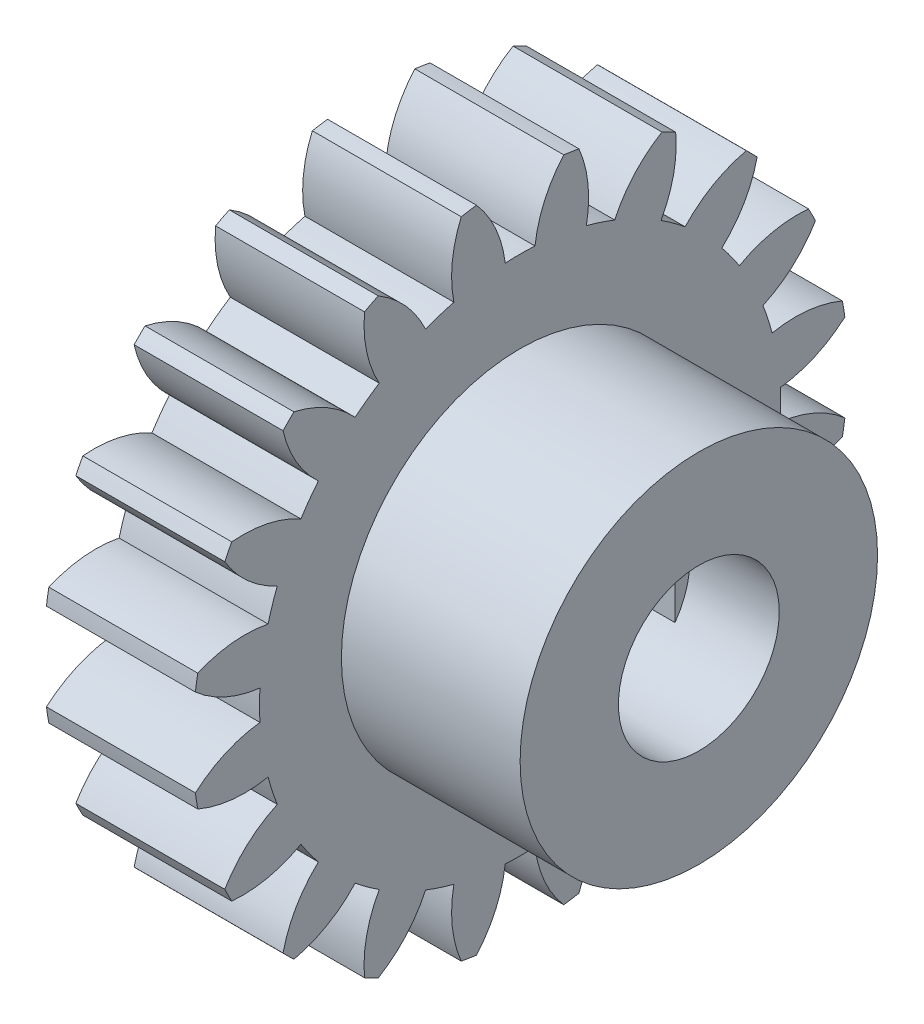
SolidWorks part; units mm, degrees
ref_plane "Plane1" through (0, 0, 0) normal (0, 0, 1) x (1, 0, 0)
ref_plane "Plane2" through (0, 0, 0) normal (0, 1, 0) x (1, 0, 0)
ref_plane "Plane3" through (0, 0, 0) normal (1, 0, 0) x (0, 0, -1)
sketch "HoldingSke" plane through (0, 0, 0) normal (0, 1, 0) x (1, 0, 0)
  line L0 (0, 0) -> (0.9397, -0.342)
  line L1 (-15, 0) -> (100, 0) construction
  line L2 (0, 0) -> (-2.1039, 2.3779)
  line L3 (0, 0) -> (-11.863, 4.5341)
  line L4 (0, 0) -> (8.1152, 2.9537)
  line L5 (0, 0) -> (-46.8476, -17.4728)
  line L6 (0, 0) -> (-8.2896, -5.593)
  line L7 (-2.1039, 2.3779) -> (8.6586, 51.2059)
  line L8 (-76.2, 54.61) -> (-75.7, 54.61)
  line L9 (-71.009, 38.7566) -> (-53.1078, 45.2721)
  line L10 (-76.2, 71.12) -> (104.1128, 71.12)
  line L11 (0, 0) -> (-10, 0)
  line L12 (-76.2, 101.6) -> (-76.162, 101.6)
  line L13 (24.9733, 27.94) -> (52.9518, 28.4284)
  line L14 (24.9733, 27.94) -> (24.9743, 27.94)
  line L15 (24.9733, 27.94) -> (100.4006, 29.5858)
  line L16 (-63.627, -1) -> (-12.827, -1)
  circle A0 centre (0, 0) radius 1.5
  circle A1 centre (0, 0) radius 8.749
  circle A2 centre (0, 0) radius 37.5
  circle A3 centre (0, 0) radius 1.5
  dimension "MHD" = 17.498
  dimension "Hub_dia" = 75
  dimension "Bore" = 3
  dimension "MBD" = 3
  dimension "Num_teeth" = 20
  dimension "Pitch" = 1
  dimension "Overall_len" = 50
  dimension "Show_teeth" = 20
  dimension "Thickness" = 10
  dimension "OAL" = 50.0001
  dimension "T_dim" = 0.5
  dimension "Ap" = 20
  dimension "H" = 19.05
  dimension "Pitch_radius" = 180.3128
  dimension "Width" = 10
  dimension "Backlash" = 0.038
  dimension "Addendum_fac" = 1
  dimension "Dedendum_fac" = 1.25
  dimension "Clearance_fac" = 0.25
  dimension "Dedendum_add" = 0.001
  dimension "Module" = 1
sketch "BasProSke" plane through (0, 0, 0) normal (0, 1, 0) x (1, 0, 0)
  line L0 (-10, 0) -> (60, 0) construction
  line L1 (0, 0) -> (0, 11)
  line L2 (0, 0) -> (5, 0)
  line L3 (5, 0) -> (5, 11)
  line L4 (5, 11) -> (0, 11)
  dimension "Thickness" = 5
  dimension "Diameter" = 22
revolve "Base-Revolve" add sketch "BasProSke" angle 360 about L0
sketch "TooCutSke" plane through (0, 0, 0) normal (1, 0, 0) x (0, 0, -1)
  line L1 (0, 0) -> (0, 107) construction
  line L2 (0, 0) -> (-0.8511, 9.9637) construction
  line L3 (0, 0) -> (-3.1206, 19.7028) construction
  line L4 (-0.8511, 9.9637) -> (-1.5603, 9.8514) construction
  arc A0 (0.4999, 8.7347) -> (-0.4999, 8.7347) centre (0, 0) ccw
  arc A1 (1.4852, 10.9249) -> (-1.4852, 10.9249) centre (0, 0) ccw
  circle A2 centre (0, 0) radius 10 construction
  circle A3 centre (0, 0) radius 9.3969 construction
  arc A4 (-0.4999, 8.7347) -> (-1.4852, 10.9249) centre (-4.4722, 8.2645) ccw
  arc A5 (1.4852, 10.9249) -> (0.4999, 8.7347) centre (4.4722, 8.2645) ccw
  dimension "Root_dia" = 17.498
  dimension "Overcut_dia" = 22.0508
  dimension "Pitch_dia" = 20
  dimension "Base_dia" = 18.7939
  dimension "Flank_rad" = 4
  dimension "Half_ang" = 9
  dimension "Half_CT" = 0.7181
extrude "ToothCut" cut sketch "TooCutSke" along normal through all
fillet "Breaks" [suppressed] radius 0.02
fillet "RootFillets" [suppressed] radius 0.251
pattern_circular "TeethCuts" count 20 over 360 about axis through (0, 0, 0) along (1, 0, 0) of "ToothCut", "RootFillets", "Breaks"
sketch "HubNeaOneSke" plane through (0, 0, 0) normal (-1, 0, 0) x (0, 0, 1)
  circle A0 centre (0, 0) radius 8.749
  dimension "Diameter" = 17.498
extrude "HubNearOne" [suppressed] add sketch "HubNeaOneSke" along normal blind 45.0001
sketch "HubNeaBotSke" plane through (0, 0, 0) normal (-1, 0, 0) x (0, 0, 1)
  circle A0 centre (0, 0) radius 8.749
  dimension "Diameter" = 17.498
extrude "HubNearBoth" [suppressed] add sketch "HubNeaBotSke" along normal blind 22.5
ref_plane "FarPln" through (5, 0, 0) normal (1, 0, 0) x (0, 0, -1)
sketch "HubFarSke" plane through (5, 0, 0) normal (1, 0, 0) x (0, 0, -1)
  circle A0 centre (0, 0) radius 8.749
  dimension "Diameter" = 17.498
extrude "HubFar" [suppressed] add sketch "HubFarSke" along normal blind 22.5
sketch "BorSke" plane through (0, 0, 0) normal (1, 0, 0) x (0, 0, -1)
  circle A0 centre (0, 0) radius 1.5
  dimension "Diameter" = 3
extrude "Bore" cut sketch "BorSke" along normal mid plane 100.0001
sketch "KeySke" plane through (0, 0, 0) normal (1, 0, 0) x (0, 0, -1)
  line L0 (-0.6, 0) -> (-0.6, 2)
  line L1 (-0.6, 2) -> (0.6, 2)
  line L2 (0.6, 2) -> (0.6, 0)
  line L3 (0, 0) -> (0, 34) construction
  line L4 (-0.6, 0) -> (0.6, 0)
  dimension "Offset" = 2
  dimension "Width" = 1.2
extrude "Keyway" [suppressed] cut sketch "KeySke" along normal mid plane 100.0001
pattern_circular "Keyway2" [suppressed] count 2 every 90 about axis through (-10, 0, 0) along (1, 0, 0)
sketch "草图1" plane through (5, 0, 0) normal (1, 0, 0) x (0, 0, -1)
  circle A0 centre (0, 0) radius 6
  dimension "D1" = 12
extrude "凸台-拉伸1" add sketch "草图1" along normal blind 6
sketch "草图2" plane through (11, 0, 0) normal (1, 0, 0) x (0, 0, -1)
  line L0 (2.2, 1.5652) -> (2.2, -1.5652)
  arc A0 (2.2, 1.5652) -> (2.2, -1.5652) centre (0, 0) ccw
  dimension "D1" = 5.4
  dimension "D2" = 2.2
extrude "切除-拉伸1" cut sketch "草图2" against normal blind 14
sketch "草图3" plane through (11, 0, 0) normal (1, 0, 0) x (0, 0, -1)
  circle A0 centre (0, 0) radius 2.7
extrude "切除-拉伸2" cut sketch "草图3" against normal blind 3
equation "' \"Module@HoldingSke\" = 6.35"
equation "' \"Num_teeth@HoldingSke\" = 12"
equation "' \"Ap@HoldingSke\" =  20"
equation "' \"Ap@HoldingSke\" = 20"
equation "' \"Width@HoldingSke\" = 0.5 * 25.4"
equation "' \"Hub_dia@HoldingSke\"= 1 * 25.4"
equation "' \"Hub_dia@HoldingSke\" = 1 * 25.4"
equation "' \"Overall_len@HoldingSke\" = 1.0 * 25.4"
equation "' \"Bore@HoldingSke\" = 0.75 * 25.4"
equation "' \"T_dim@HoldingSke\" = 0.1 * 25.4"
equation "' \"Width@KeySke\" = 0.25 * 25.4"
equation "' \"Show_teeth@HoldingSke\" = 13"
equation "' \"Backlash@HoldingSke\" = 0.009 * 25.4"
equation "' \"Addendum_fac@HoldingSke\" = 1.0"
equation "' \"Dedendum_fac@HoldingSke\" = 1.25"
equation "' \"Dedendum_add@HoldingSke\" = 0.00005 * 25.4"
equation "' \"Clearance_fac@HoldingSke\" = 0.25"
equation "\"Pitch@HoldingSke\" = 1 / \"Module@HoldingSke\""
equation "\"Overcut_dia@TooCutSke\" = (\"Num_teeth@HoldingSke\" + 2 * \"Addendum_fac@HoldingSke\") / \"Pitch@HoldingSke\" + 0.002 * 25.4"
equation "\"Pitch_dia@TooCutSke\" = \"Num_teeth@HoldingSke\" / \"Pitch@HoldingSke\""
equation "\"Base_dia@TooCutSke\" = \"Num_teeth@HoldingSke\" / \"Pitch@HoldingSke\" * cos((\"Ap@HoldingSke\"  * 3.14159265 / 180))"
equation "\"Root_dia@TooCutSke\" = (\"Num_teeth@HoldingSke\" + 2) / \"Pitch@HoldingSke\" - 2 * (\"Addendum_fac@HoldingSke\" + \"Dedendum_fac@HoldingSke\") / \"Pitch@HoldingSke\" - \"Dedendum_add@HoldingSke\" * 2"
equation "\"Half_ang@TooCutSke\" = 180 / \"Num_teeth@HoldingSke\""
equation "\"Half_CT@TooCutSke\" = \"Num_teeth@HoldingSke\" / \"Pitch@HoldingSke\" * sin((3.14159265 / 2 / \"Num_teeth@HoldingSke\")) / 2 - 7 * \"Backlash@HoldingSke\" / 4"
equation "\"Flank_rad@TooCutSke\" = \"Num_teeth@HoldingSke\" / \"Pitch@HoldingSke\" / 5"
equation "\"Radius@RootFillets\" = \"Clearance_fac@HoldingSke\" / \"Pitch@HoldingSke\" + \"Dedendum_add@HoldingSke\""
equation "\"Break_rad@Breaks\" = 0.02 / \"Pitch@HoldingSke\""
equation "\"Thickness@HoldingSke\" = \"Width@HoldingSke\""
equation "\"OAL@HoldingSke\" = \"Thickness@HoldingSke\""
equation "\"MHD@HoldingSke\" = (\"Num_teeth@HoldingSke\" + 2) / \"Pitch@HoldingSke\" - 2 * (\"Addendum_fac@HoldingSke\" + \"Dedendum_fac@HoldingSke\")  / \"Pitch@HoldingSke\" - \"Dedendum_add@HoldingSke\" * 2"
equation "\"MBD@HoldingSke\" = (\"Num_teeth@HoldingSke\" + 2) / \"Pitch@HoldingSke\" - 2 * (\"Addendum_fac@HoldingSke\" + \"Dedendum_fac@HoldingSke\")  / \"Pitch@HoldingSke\" - \"Dedendum_add@HoldingSke\" * 2 - 0.002 * 25.4"
equation "\"MHD@HoldingSke\" = ((sgn( \"MHD@HoldingSke\" - \"Hub_dia@HoldingSke\" )-1)*( \"MHD@HoldingSke\" - \"Hub_dia@HoldingSke\" ))/-2+ \"Hub_dia@HoldingSke\""
equation "\"MBD@HoldingSke\" = ((sgn( \"MBD@HoldingSke\" - \"Bore@HoldingSke\" )-1)*( \"MBD@HoldingSke\" - \"Bore@HoldingSke\" ))/-2+ \"Bore@HoldingSke\""
equation "\"OAL@HoldingSke\" = ((sgn( \"OAL@HoldingSke\" - \"Overall_len@HoldingSke\" )+1)*( \"OAL@HoldingSke\" - \"Overall_len@HoldingSke\" ))/2 + \"Overall_len@HoldingSke\" + 0.000002 * 25.4"
equation "\"Num_teeth@TeethCuts\" = int( \"Show_teeth@HoldingSke\" ) + 1"
equation "\"Num_teeth@TeethCuts\" = ((sgn( \"Num_teeth@TeethCuts\" - \"Num_teeth@HoldingSke\" )-1)*( \"Num_teeth@TeethCuts\" - \"Num_teeth@HoldingSke\" ))/-2+ \"Num_teeth@HoldingSke\""
equation "\"Num_teeth@TeethCuts\" = ((sgn( \"Num_teeth@TeethCuts\" - 2.0)+1)*( \"Num_teeth@TeethCuts\" - 2.0))/2 +2.0"
equation "\"Angle@TeethCuts\" = 360.0 / \"Num_teeth@HoldingSke\""
equation "\"Diameter@BasProSke\" = (\"Num_teeth@HoldingSke\" + 2 * \"Addendum_fac@HoldingSke\") / \"Pitch@HoldingSke\""
equation "' \"Fillet_rad@BasProSke\" =  \"Thickness@HoldingSke\" * 0.05"
equation "' \"Fillet_rad@BasProSke\" = \"Thickness@HoldingSke\" * 0.05"
equation "\"MHD@HoldingSke\" = ((sgn( \"MHD@HoldingSke\" - \"Root_dia@TooCutSke\" )-1)*( \"MHD@HoldingSke\" - \"Root_dia@TooCutSke\" ))/-2+ \"Root_dia@TooCutSke\""
equation "\"Diameter@HubNeaOneSke\" = \"MHD@HoldingSke\""
equation "\"Length@HubNearOne\" = \"OAL@HoldingSke\" - \"Thickness@BasProSke\""
equation "\"Diameter@HubNeaBotSke\" = \"MHD@HoldingSke\""
equation "\"Length@HubNearBoth\" = ( \"OAL@HoldingSke\" - \"Thickness@BasProSke\" ) / 2.0"
equation "\"Thickness@FarPln\" = \"Thickness@BasProSke\""
equation "\"Diameter@HubFarSke\" = \"MHD@HoldingSke\""
equation "\"Length@HubFar\" = ( \"OAL@HoldingSke\" - \"Thickness@BasProSke\" ) / 2.0"
equation "\"D1@Bore\" = \"OAL@HoldingSke\" * 2.0"
equation "\"D1@Keyway\" = \"OAL@HoldingSke\" * 2.0"
equation "\"Offset@KeySke\" = \"T_dim@HoldingSke\" + \"MBD@HoldingSke\" / 2.0"
